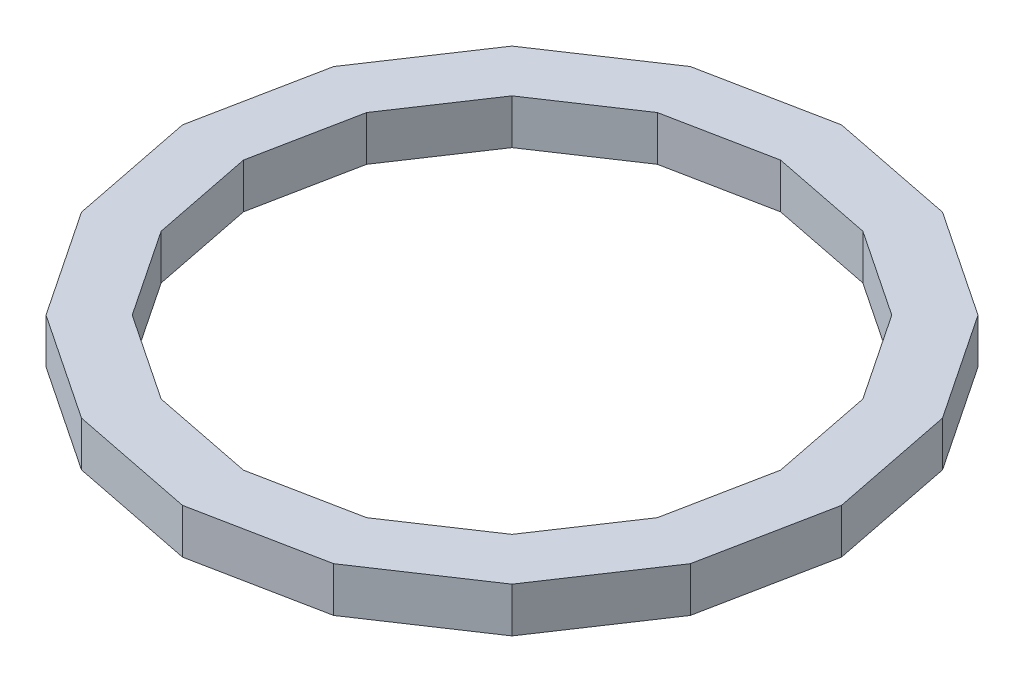
SolidWorks part; units mm, degrees
ref_plane "Front Plane" through (0, 0, 0) normal (0, 0, 1) x (1, 0, 0)
ref_plane "Top Plane" through (0, 0, 0) normal (0, 1, 0) x (1, 0, 0)
ref_plane "Right Plane" through (0, 0, 0) normal (1, 0, 0) x (0, 0, -1)
sketch "Sketch1" plane through (0, 0, 0) normal (0, 1, 0) x (1, 0, 0)
  line L1 (139.9608, 0) -> (129.3069, 53.5607)
  line L2 (129.3069, 53.5607) -> (98.9672, 98.9672)
  line L3 (98.9672, 98.9672) -> (53.5607, 129.3069)
  line L4 (53.5607, 129.3069) -> (0, 139.9608)
  line L5 (0, 139.9608) -> (-53.5607, 129.3069)
  line L6 (-53.5607, 129.3069) -> (-98.9672, 98.9672)
  line L7 (-98.9672, 98.9672) -> (-129.3069, 53.5607)
  line L8 (-129.3069, 53.5607) -> (-139.9608, 0)
  line L9 (-139.9608, 0) -> (-129.3069, -53.5607)
  line L10 (-129.3069, -53.5607) -> (-98.9672, -98.9672)
  line L11 (-98.9672, -98.9672) -> (-53.5607, -129.3069)
  line L12 (-53.5607, -129.3069) -> (0, -139.9608)
  line L13 (0, -139.9608) -> (53.5607, -129.3069)
  line L14 (53.5607, -129.3069) -> (98.9672, -98.9672)
  line L15 (98.9672, -98.9672) -> (129.3069, -53.5607)
  line L16 (129.3069, -53.5607) -> (139.9608, 0)
  line L17 (114.0632, 0) -> (105.3807, 43.6501)
  line L18 (105.3807, 43.6501) -> (80.6549, 80.6549)
  line L19 (80.6549, 80.6549) -> (43.6501, 105.3807)
  line L20 (43.6501, 105.3807) -> (0, 114.0632)
  line L21 (0, 114.0632) -> (-43.6501, 105.3807)
  line L22 (-43.6501, 105.3807) -> (-80.6549, 80.6549)
  line L23 (-80.6549, 80.6549) -> (-105.3807, 43.6501)
  line L24 (-105.3807, 43.6501) -> (-114.0632, 0)
  line L25 (-114.0632, 0) -> (-105.3807, -43.6501)
  line L26 (-105.3807, -43.6501) -> (-80.6549, -80.6549)
  line L27 (-80.6549, -80.6549) -> (-43.6501, -105.3807)
  line L28 (-43.6501, -105.3807) -> (0, -114.0632)
  line L29 (0, -114.0632) -> (43.6501, -105.3807)
  line L30 (43.6501, -105.3807) -> (80.6549, -80.6549)
  line L31 (80.6549, -80.6549) -> (105.3807, -43.6501)
  line L32 (105.3807, -43.6501) -> (114.0632, 0)
  circle A0 centre (0, 0) radius 137.2715 construction
  circle A1 centre (0, 0) radius 111.8715 construction
  dimension "D1" = 25.4
  dimension "D2" = 54.61
extrude "Boss-Extrude1" add sketch "Sketch1" along normal blind 19.05
